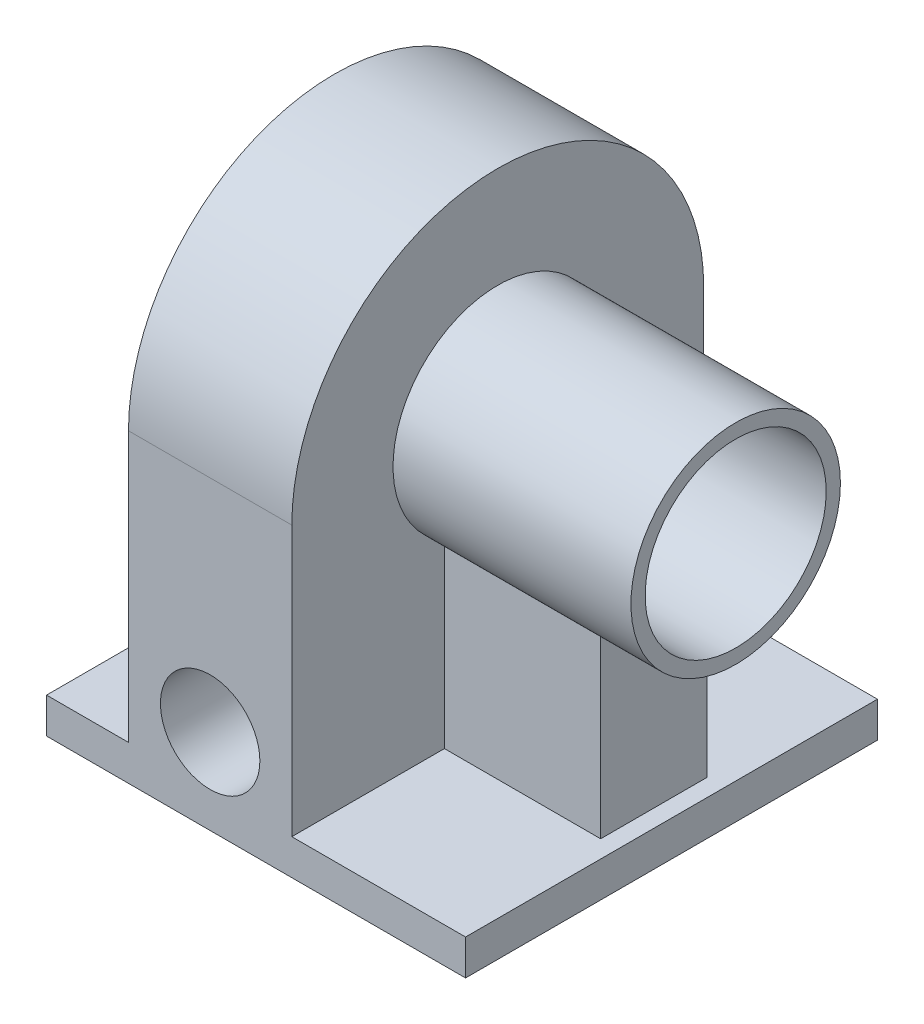
SolidWorks part; units mm, degrees
ref_plane "Front Plane" through (0, 0, 0) normal (0, 0, 1) x (1, 0, 0)
ref_plane "Top Plane" through (0, 0, 0) normal (0, 1, 0) x (1, 0, 0)
ref_plane "Right Plane" through (0, 0, 0) normal (1, 0, 0) x (0, 0, -1)
sketch "Sketch1" plane through (0, 0, 0) normal (0, 0, 1) x (1, 0, 0)
  line L0 (-59.0733, 0) -> (-59.0733, 10)
  line L1 (-59.0733, 10) -> (58.9267, 10)
  line L2 (58.9267, 10) -> (58.9267, 0)
  line L3 (58.9267, 0) -> (-59.0733, 0)
  dimension "D1" = 118
  dimension "D2" = 10
extrude "Boss-Extrude1" add sketch "Sketch1" against normal blind 116
ref_plane "Plane1" through (10, 0, 0) normal (1, 0, 0) x (0, 0, -1)
sketch "Sketch2" plane through (10, 0, 0) normal (1, 0, 0) x (0, 0, -1)
  line L0 (0, 10) -> (116, 10)
  line L1 (58, 10) -> (58, 86) construction
  line L2 (0, 10) -> (0, 86)
  line L3 (116, 10) -> (116, 86)
  line L5 (116, 0) -> (0, 0) construction
  arc A0 (0, 10) -> (116, 10) centre (58, 10) ccw
  arc A1 (116, 86) -> (0, 86) centre (58, 86) ccw
  point P6 (58, 48)
  dimension "D2" = 58
  dimension "D1" = 86
extrude "Boss-Extrude2" add sketch "Sketch2" against normal blind 46
sketch "Sketch3" plane through (0, 0, 0) normal (0, 0, 1) x (1, 0, 0)
  line L0 (-36, 10) -> (-36, 86) construction
  line L1 (-59.0733, 0) -> (58.9267, 0) construction
  circle A0 centre (-13, 24) radius 14
  point P4 (0, 0)
  point P6 (-12.7382, 25.4682)
  dimension "D1" = 23
  dimension "D2" = 24
extrude "Cut-Extrude1" cut sketch "Sketch3" against normal through all
sketch "Sketch4" plane through (10, 0, 0) normal (1, 0, 0) x (0, 0, -1)
  circle A0 centre (58, 86) radius 29.5
  circle A1 centre (58, 86) radius 25.5
  dimension "D1" = 59
  dimension "D2" = 51
extrude "Boss-Extrude3" add sketch "Sketch4" along normal blind 67
sketch "Sketch6" plane through (0, 10, 0) normal (0, 1, 0) x (1, 0, 0)
  line L0 (10, 72.9751) -> (10, 42.9751)
  line L7 (54, 72.9751) -> (54, 42.9751)
  line L12 (10, 42.9751) -> (54, 42.9751)
  line L13 (10, 72.9751) -> (54, 72.9751)
  dimension "D1" = 44
extrude "Boss-Extrude4" add sketch "Sketch6" along normal blind 55
sketch "Sketch7" plane through (54, 0, 0) normal (1, 0, 0) x (0, 0, -1)
  line L0 (43.5345, 65) -> (72.4655, 65)
  arc A0 (72.4655, 65) -> (43.5345, 65) centre (58, 86) cw
extrude "Cut-Extrude2" cut sketch "Sketch7" against normal blind 44
